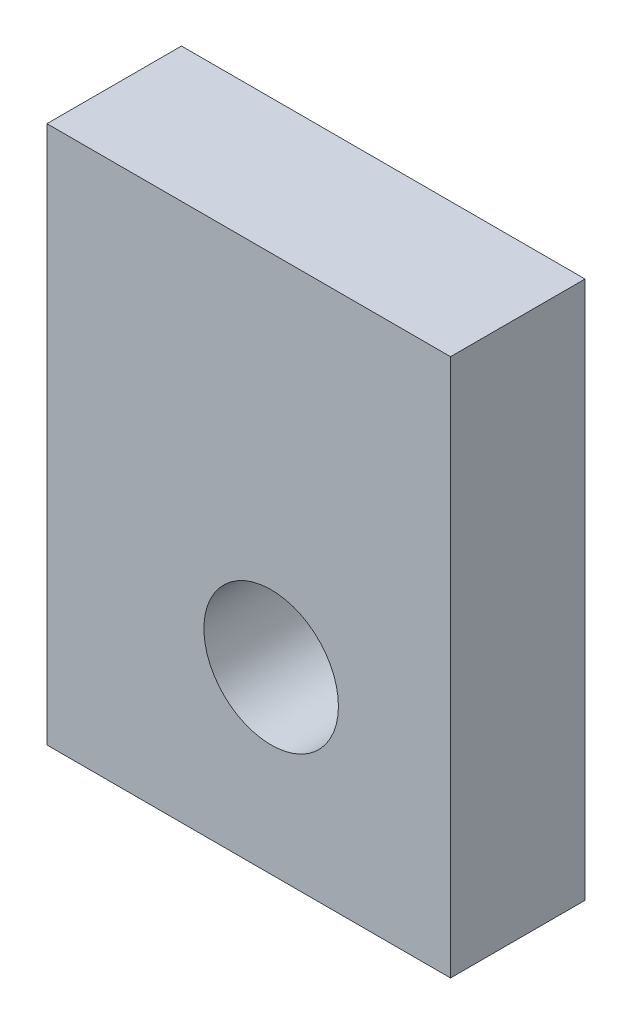
SolidWorks part; units mm, degrees
ref_plane "Спереди" through (0, 0, 0) normal (0, 0, 1) x (1, 0, 0)
ref_plane "Сверху" through (0, 0, 0) normal (0, 1, 0) x (1, 0, 0)
ref_plane "Справа" through (0, 0, 0) normal (1, 0, 0) x (0, 0, -1)
other "Configuration Table"
sketch "Эскиз1" plane through (0, 0, 0) normal (0, 0, 1) x (1, 0, 0)
  line L0 (4.5, 12) -> (4.5, 0) construction
  line L1 (0, 0) -> (9, 0)
  line L2 (0, 0) -> (0, 12)
  line L3 (0, 12) -> (9, 12)
  line L4 (9, 0) -> (9, 12)
  line L5 (0, 6) -> (9, 6) construction
  dimension "D1" = 9
  dimension "D2" = 12
extrude "Бобышка-Вытянуть1" add sketch "Эскиз1" along normal blind 3
sketch "Эскиз2" plane through (0, 0, 3) normal (0, 0, 1) x (1, 0, 0)
  line L0 (0, 0) -> (9, 0) construction
  line L7 (0, 12) -> (0, 0) construction
  circle A0 centre (5, 4) radius 1.5
  dimension "D1" = 3
  dimension "D2" = 4
  dimension "D3" = 5
extrude "Вырез-Вытянуть1" cut sketch "Эскиз2" against normal through all
